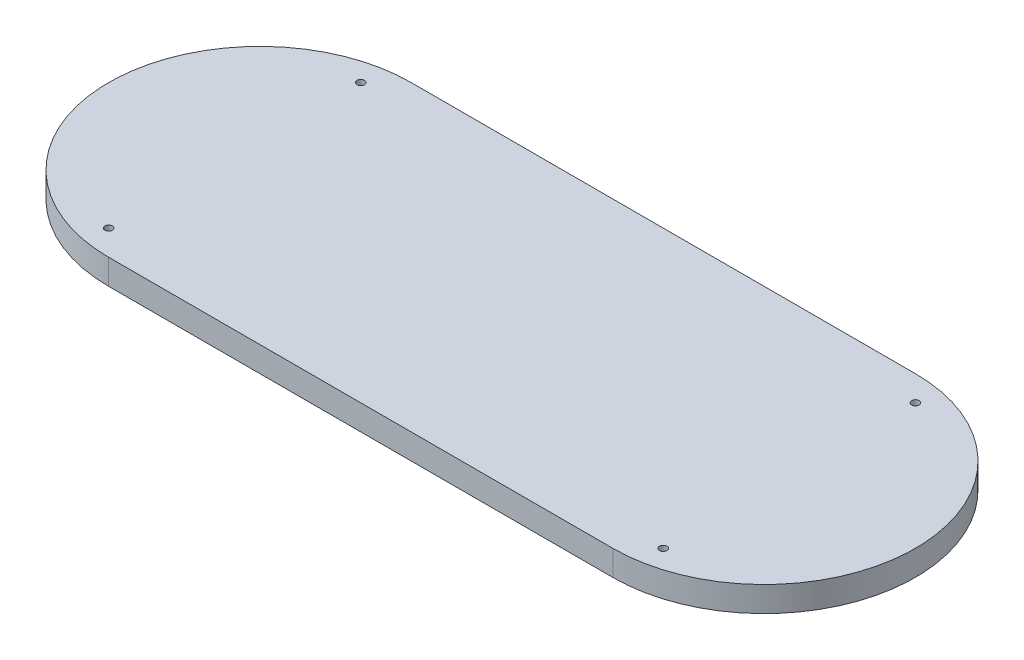
SolidWorks part; units mm, degrees
ref_plane "Front Plane" through (0, 0, 0) normal (0, 0, 1) x (1, 0, 0)
ref_plane "Top Plane" through (0, 0, 0) normal (0, 1, 0) x (1, 0, 0)
ref_plane "Right Plane" through (0, 0, 0) normal (1, 0, 0) x (0, 0, -1)
sketch "Sketch1" plane through (0, 0, 0) normal (0, 1, 0) x (1, 0, 0)
  line L0 (-100, 0) -> (100, 0) construction
  line L1 (-100, 60) -> (100, 60)
  line L2 (-100, -60) -> (100, -60)
  arc A0 (-100, 60) -> (-100, -60) centre (-100, 0) ccw
  arc A1 (100, -60) -> (100, 60) centre (100, 0) ccw
  point P3 (0, 0)
  point P8 (0, 0)
  dimension "D2" = 60
  dimension "D1" = 200
extrude "Boss-Extrude1" add sketch "Sketch1" along normal blind 10
sketch "Sketch2" plane through (0, 10, 0) normal (0, 1, 0) x (1, 0, 0)
  line L0 (-110, 50) -> (110, 50) construction
  line L1 (-110, 50) -> (-110, -50) construction
  circle A0 centre (-110, 50) radius 1.5
  circle A1 centre (-110, -50) radius 1.5
  circle A2 centre (110, -50) radius 1.5
  circle A3 centre (110, 50) radius 1.5
  point P8 (0, 50)
  point P9 (-110, 0)
  dimension "D1" = 3
  dimension "D2" = 220
  dimension "D3" = 100
extrude "Cut-Extrude1" cut sketch "Sketch2" against normal through all
